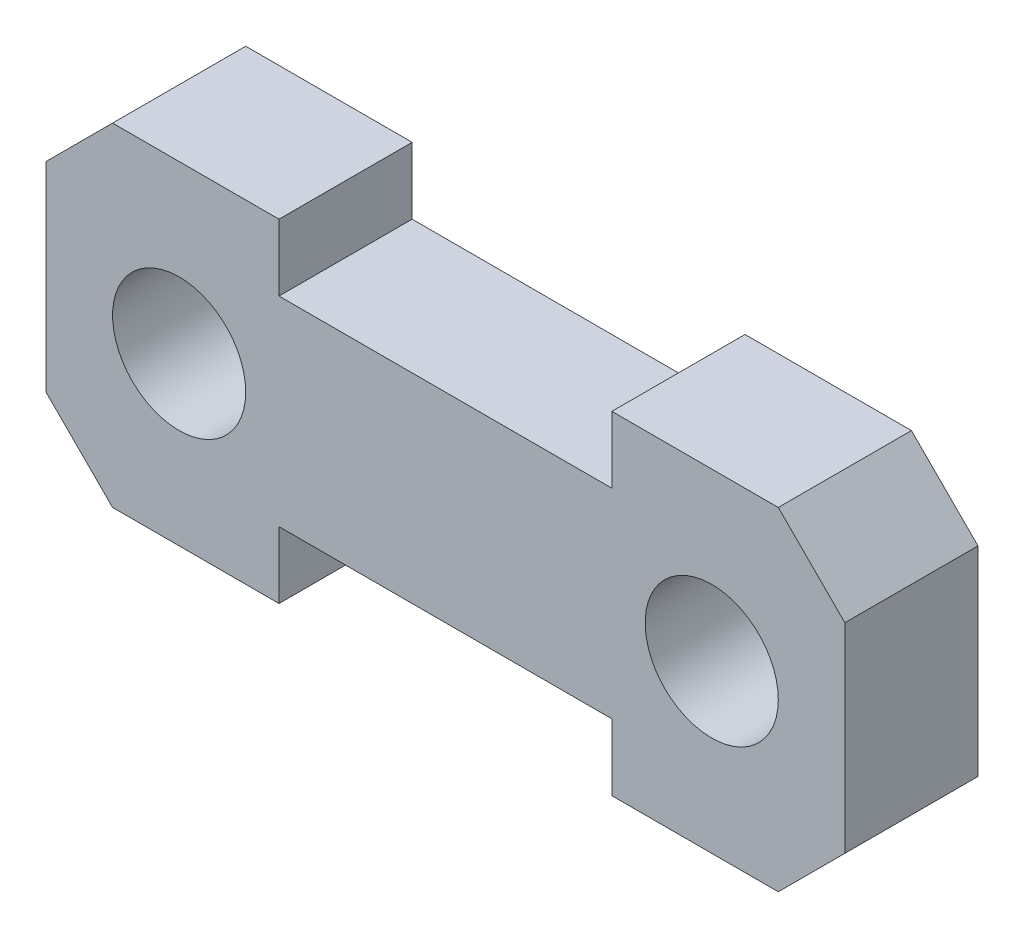
SolidWorks part; units mm, degrees
ref_plane "前视基准面" through (0, 0, 0) normal (0, 0, 1) x (1, 0, 0)
ref_plane "上视基准面" through (0, 0, 0) normal (0, 1, 0) x (1, 0, 0)
ref_plane "右视基准面" through (0, 0, 0) normal (1, 0, 0) x (0, 0, -1)
sketch "草图1" plane through (0, 0, 0) normal (0, 0, 1) x (1, 0, 0)
  line L0 (-2.5, 2.5) -> (-2.5, 1.5)
  line L1 (-5, 2.5) -> (-2.5, 2.5)
  line L2 (-6, 1.5) -> (-6, -1.5)
  line L3 (-5, -2.5) -> (-2.5, -2.5)
  line L4 (6, 1.5) -> (6, -1.5)
  line L5 (-6, 2.5) -> (6, -2.5) construction
  line L6 (-6, -2.5) -> (6, 2.5) construction
  line L7 (-2.5, 1.5) -> (2.5, 1.5)
  line L8 (2.5, 2.5) -> (2.5, 1.5)
  line L9 (0, 0) -> (1.9919, 0) construction
  line L10 (2.5, -2.5) -> (2.5, -1.5)
  line L11 (-2.5, -1.5) -> (2.5, -1.5)
  line L12 (-2.5, -2.5) -> (-2.5, -1.5)
  line L13 (2.5, 2.5) -> (5, 2.5)
  line L14 (2.5, -2.5) -> (5, -2.5)
  line L15 (-6, -1.5) -> (-5, -2.5)
  line L16 (-6, 1.5) -> (-5, 2.5)
  line L17 (5, 2.5) -> (6, 1.5)
  line L18 (5, -2.5) -> (6, -1.5)
  circle A0 centre (-4, 0) radius 1
  circle A1 centre (4, 0) radius 1
  point P0 (0, 0)
  dimension "D3" = 8
  dimension "D4" = 2
  dimension "D1" = 5
  dimension "D2" = 12
  dimension "D5" = 4
  dimension "D6" = 3
  dimension "D7" = 5
  dimension "D8" = 2.5
extrude "凸台-拉伸1" add sketch "草图1" along normal blind 2
